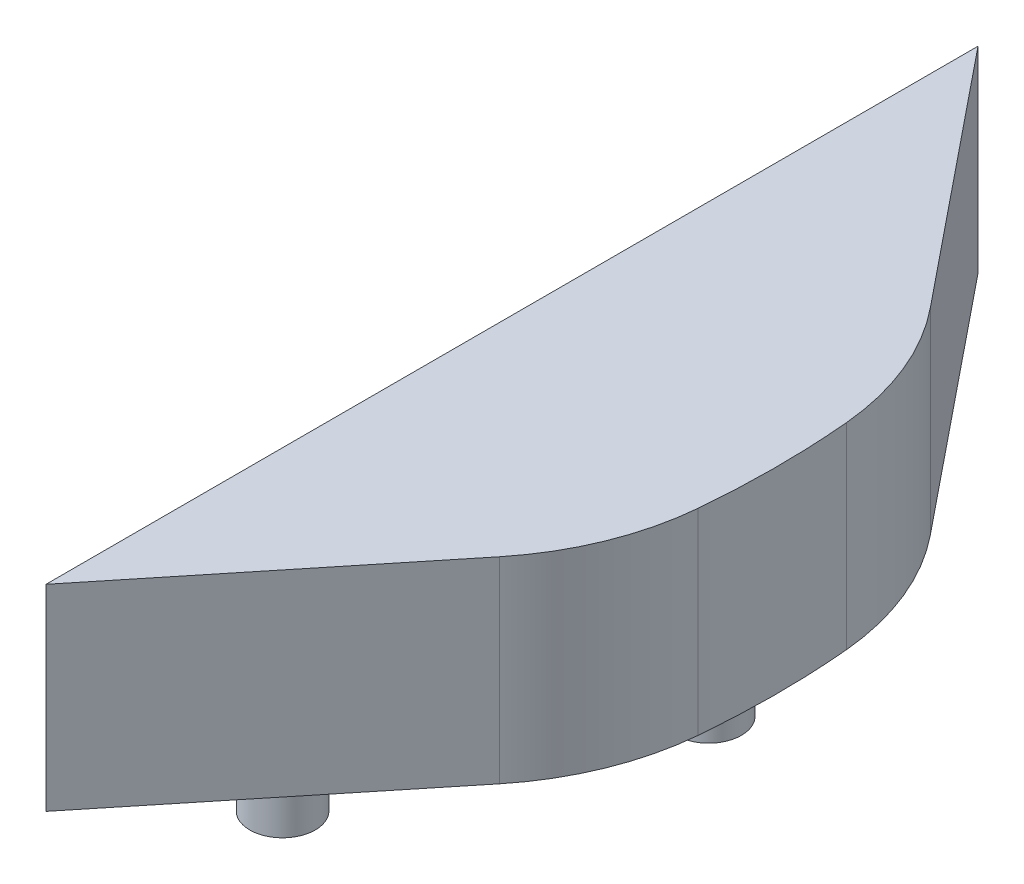
SolidWorks part; units mm, degrees
material "ABS"
ref_plane "Front Plane" through (0, 0, 0) normal (0, 0, 1) x (1, 0, 0)
ref_plane "Top Plane" through (0, 0, 0) normal (0, 1, 0) x (1, 0, 0)
ref_plane "Right Plane" through (0, 0, 0) normal (1, 0, 0) x (0, 0, -1)
sketch "Sketch3" plane through (0, 0, 0) normal (0, 1, 0) x (1, 0, 0)
  line L0 (0, 90.2726) -> (0, -90.2726)
  ellipse E0 centre (0, 0) end of major axis (0, 90.2726) minor radius 51.0637 (0, -90.2726) -> (0, 90.2726) ccw
extrude "Boss-Extrude2" add sketch "Sketch3" along normal blind 38.1
sketch "Sketch4" plane through (0, 0, 0) normal (0, -1, 0) x (-1, 0, 0)
  line L0 (0, 90.2726) -> (0, -90.2726) construction
  circle A0 centre (-12.7, -57.15) radius 6.35
  circle A1 centre (-12.7, 57.15) radius 6.35
  circle A2 centre (-38.1, 0) radius 6.35
  dimension "D1" = 12.7
  dimension "D2" = 57.15
  dimension "D3" = 57.15
  dimension "D4" = 25.4
  dimension "D5" = 25.4
  dimension "D6" = 12.7
extrude "Boss-Extrude3" add sketch "Sketch4" along normal blind 10.16
sketch "Sketch5" plane through (0, 0, 0) normal (0, -1, 0) x (-1, 0, 0)
  line L0 (0, -90.2726) -> (-47.9482, -31.0493)
  line L1 (0, 90.2726) -> (-47.9482, 31.0493)
  line L2 (-47.9482, 31.0493) -> (-64.2839, 60.6609)
  line L3 (-64.2839, 60.6609) -> (-1.5021, 110.7132)
  line L4 (-1.5021, 110.7132) -> (0, 90.2726)
  line L5 (-47.9482, -31.0493) -> (-73.0558, -65.5802)
  line L6 (-73.0558, -65.5802) -> (-28.8617, -122.2421)
  line L7 (-28.8617, -122.2421) -> (0, -90.2726)
  ellipse E0 centre (0, 0) end of major axis (0, 90.2726) minor radius 51.0637 (0, 90.2726) -> (0, -90.2726) ccw construction
  dimension "D1" = 76.2
extrude "Cut-Extrude1" cut sketch "Sketch5" against normal blind 72.136
fillet "Fillet1" radius 50.8 2 edges at (47.9482, 19.05, -31.0493) (47.9482, 19.05, 31.0493)
